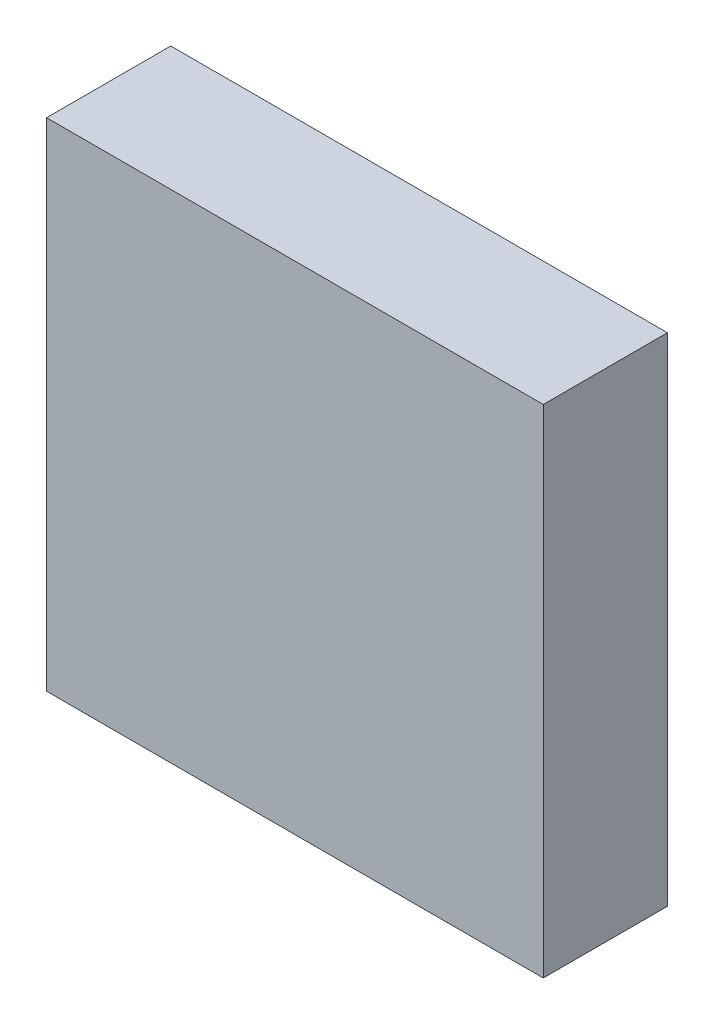
SolidWorks part; units mm, degrees
material "Carvalho"
ref_plane "Plano frontal" through (0, 0, 0) normal (0, 0, 1) x (1, 0, 0)
ref_plane "Plano superior" through (0, 0, 0) normal (0, 1, 0) x (1, 0, 0)
ref_plane "Plano direito" through (0, 0, 0) normal (1, 0, 0) x (0, 0, -1)
sketch "Esboço1" plane through (0, 0, 0) normal (0, 0, 1) x (1, 0, 0)
  line L1 (0, 0) -> (200, 0)
  line L2 (0, 0) -> (0, 200)
  line L3 (0, 200) -> (200, 200)
  line L4 (200, 0) -> (200, 200)
  dimension "D1" = 200
  dimension "D2" = 200
extrude "Ressalto-extrusão1" add sketch "Esboço1" along normal blind 50
sketch "Esboço2" plane through (0, 0, 0) normal (0, 0, -1) x (-1, 0, 0)
  line L0 (-100, 0) -> (-100, 200) construction
  line L1 (0, 0) -> (-200, 0) construction
  line L2 (-200, 200) -> (0, 200) construction
  line L3 (-200, 100) -> (0, 100) construction
  line L4 (-200, 0) -> (-200, 200) construction
  line L5 (0, 200) -> (0, 0) construction
  point P12 (-100, 100)
sketch "Esboço3" plane through (0, 0, 0) normal (0, 0, -1) x (-1, 0, 0)
  line L0 (-100, 200) -> (-100, -7.0341) construction
  line L10 (-160.5, 176.55) -> (-160.5, 177.05)
  line L12 (-179.5, 176.55) -> (-179.5, 177.05)
  line L18 (-179.5, 176.55) -> (-179.5, 174.65)
  line L19 (-179.5, 174.65) -> (-160.5, 174.65)
  line L20 (-160.5, 176.55) -> (-160.5, 174.65)
  line L22 (-179.5, 177.05) -> (-179.5, 178.95)
  line L23 (-179.5, 178.95) -> (-160.5, 178.95)
  line L24 (-160.5, 177.05) -> (-160.5, 178.95)
  line L25 (-200, 200) -> (0, 200) construction
  line L26 (-100, -7.0341) -> (-211.574, 100) construction
  line L27 (-211.574, 100) -> (19.3654, 100) construction
  line L28 (-39.5, 177.05) -> (-39.5, 178.95)
  line L29 (-20.5, 178.95) -> (-39.5, 178.95)
  line L30 (-20.5, 177.05) -> (-20.5, 178.95)
  line L31 (-39.5, 176.55) -> (-39.5, 174.65)
  line L32 (-20.5, 174.65) -> (-39.5, 174.65)
  line L33 (-20.5, 176.55) -> (-20.5, 174.65)
  line L34 (-20.5, 176.55) -> (-20.5, 177.05)
  line L35 (-39.5, 176.55) -> (-39.5, 177.05)
  line L40 (-39.5, 23.45) -> (-39.5, 22.95)
  line L41 (-20.5, 23.45) -> (-20.5, 22.95)
  line L42 (-20.5, 23.45) -> (-20.5, 25.35)
  line L43 (-20.5, 25.35) -> (-39.5, 25.35)
  line L44 (-39.5, 23.45) -> (-39.5, 25.35)
  line L45 (-20.5, 22.95) -> (-20.5, 21.05)
  line L46 (-20.5, 21.05) -> (-39.5, 21.05)
  line L47 (-39.5, 22.95) -> (-39.5, 21.05)
  line L48 (-160.5, 22.95) -> (-160.5, 21.05)
  line L49 (-179.5, 21.05) -> (-160.5, 21.05)
  line L50 (-179.5, 22.95) -> (-179.5, 21.05)
  line L51 (-160.5, 23.45) -> (-160.5, 25.35)
  line L52 (-179.5, 25.35) -> (-160.5, 25.35)
  line L53 (-179.5, 23.45) -> (-179.5, 25.35)
  line L54 (-179.5, 23.45) -> (-179.5, 22.95)
  line L55 (-160.5, 23.45) -> (-160.5, 22.95)
  dimension "D1" = 1.9
  dimension "D2" = 1.9
extrude "Corte-extrusão1" cut sketch "Esboço3" against normal blind 7
